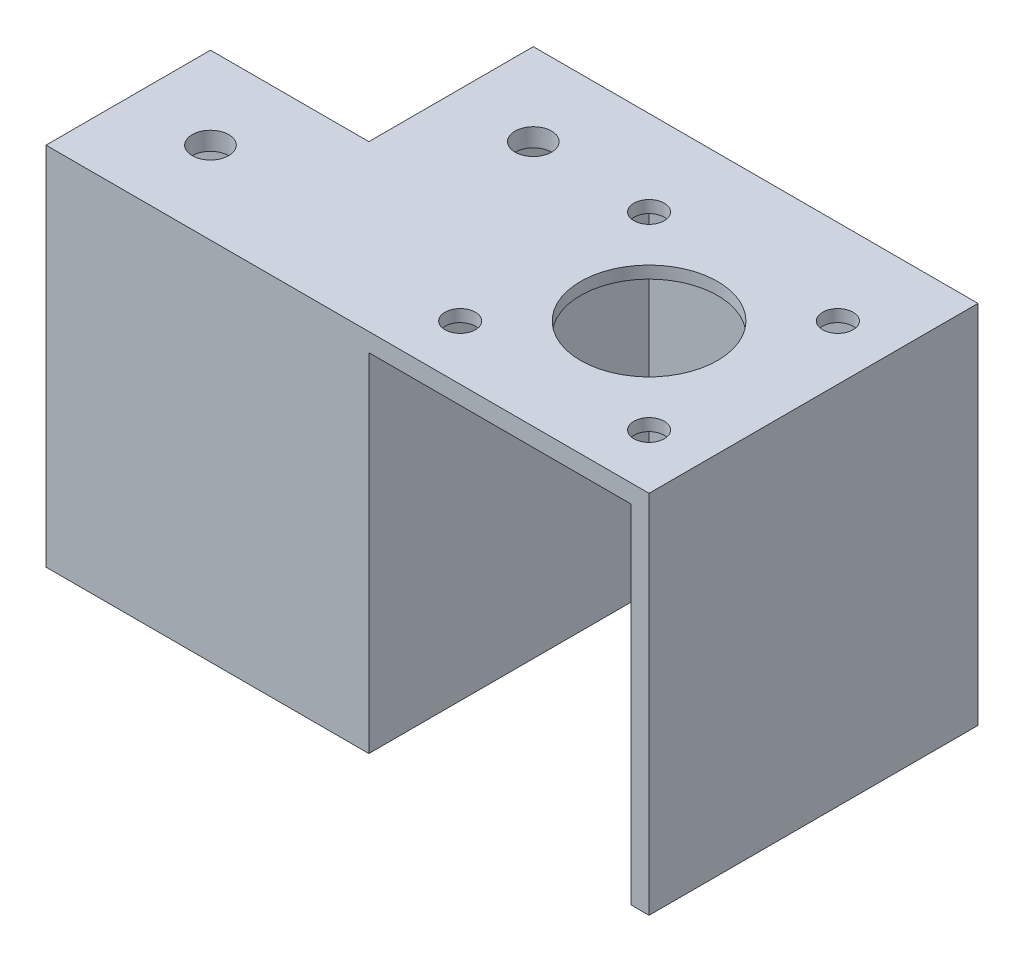
SolidWorks part; units mm, degrees
ref_plane "Front Plane" through (0, 0, 0) normal (0, 0, 1) x (1, 0, 0)
ref_plane "Top Plane" through (0, 0, 0) normal (0, 1, 0) x (1, 0, 0)
ref_plane "Right Plane" through (0, 0, 0) normal (1, 0, 0) x (0, 0, -1)
sketch "Sketch1" plane through (0, 0, 0) normal (0, 1, 0) x (1, 0, 0)
  line L0 (-15.5, 15.5) -> (15.5, 15.5) construction
  line L1 (-21.5, -21.5) -> (21.5, -21.5) construction
  line L2 (-21.5, -21.5) -> (-21.5, 21.5) construction
  line L3 (-21.5, 21.5) -> (21.5, 21.5) construction
  line L4 (21.5, -21.5) -> (21.5, 21.5) construction
  line L5 (-21.5, -21.5) -> (21.5, 21.5) construction
  line L6 (-21.5, 21.5) -> (21.5, -21.5) construction
  line L7 (-21.5, 0) -> (21.5, 0) construction
  line L8 (-21.5, 21.5) -> (-24.5, 29.5) construction
  line L10 (-24.5, 29.5) -> (48.5, 29.5)
  line L11 (-24.5, 29.5) -> (-24.5, -24.5)
  line L12 (-24.5, -24.5) -> (48.5, -24.5)
  line L13 (48.5, 29.5) -> (48.5, 2.5)
  line L14 (48.5, -24.5) -> (74.5, -24.5)
  line L16 (48.5, 2.5) -> (74.5, 2.5)
  line L17 (74.5, -24.5) -> (74.5, 2.5)
  circle A0 centre (15.5, 15.5) radius 2.5
  circle A1 centre (-15.5, 15.5) radius 2.5
  circle A2 centre (15.5, -15.5) radius 2.5
  circle A3 centre (-15.5, -15.5) radius 2.5
  circle A4 centre (0, 0) radius 11.25
  point P0 (0, 0)
  point P26 (74.5, -11)
  dimension "D3" = 5
  dimension "D8" = 22.5
  dimension "D1" = 43
  dimension "D2" = 31
  dimension "D4" = 8
  dimension "D5" = 3
  dimension "D6" = 3
  dimension "D7" = 27
  dimension "D9" = 27
  dimension "D10" = 26
extrude "Boss-Extrude1" add sketch "Sketch1" against normal blind 60 contours L13 L10 L11 L12 A2 A1 A0 A3
sketch "Sketch2" plane through (0, -60, 0) normal (0, -1, 0) x (1, 0, 0)
  line L0 (21.5, 21.5) -> (21.5, -21.5) construction
  line L1 (-21.5, -21.5) -> (21.5, -21.5) construction
  line L2 (-21.5, 21.5) -> (-21.5, -21.5) construction
  line L3 (-21.5, 21.5) -> (21.5, 21.5) construction
  line L4 (21.5, 21.5) -> (21.5, -21.5)
  line L5 (-21.5, -21.5) -> (21.5, -21.5)
  line L6 (-21.5, 21.5) -> (-21.5, -21.5)
  line L7 (-21.5, 21.5) -> (21.5, 21.5)
extrude "Cut-Extrude1" cut sketch "Sketch2" against normal offset from surface (58 mm away) 2 up to face at (0, 0, 11.25)
sketch "Sketch3" plane through (0, 0, -29.5) normal (0, 0, -1) x (-1, 0, 0)
  line L0 (24.5, 0) -> (-48.5, 0) construction
  line L1 (-45.5, -3) -> (-24.5, -3)
  line L2 (-45.5, -3) -> (-45.5, -24)
  line L3 (-45.5, -24) -> (-24.5, -24)
  line L4 (-24.5, -3) -> (-24.5, -24)
  line L5 (-48.5, -60) -> (-48.5, 0) construction
  dimension "D1" = 3
  dimension "D2" = 3
  dimension "D3" = 21
extrude "Cut-Extrude2" cut sketch "Sketch3" against normal offset from surface (51 mm away) 3 up to face at (25, -30, 24.5)
sketch "Sketch4" plane through (74.5, 0, 0) normal (1, 0, 0) x (0, 0, -1)
  line L0 (29.5, 0) -> (2.5, 0) construction
  line L1 (-0.5, -3) -> (-21.5, -3)
  line L2 (-0.5, -3) -> (-0.5, -24)
  line L3 (-0.5, -24) -> (-21.5, -24)
  line L4 (-21.5, -3) -> (-21.5, -24)
  line L6 (-24.5, -60) -> (-24.5, 0) construction
  dimension "D1" = 21
  dimension "D2" = 3
  dimension "D3" = 3
extrude "Cut-Extrude3" cut sketch "Sketch4" against normal up to surface (50 mm away) up to face at (24.5, -13.5, -4)
sketch "Sketch6" plane through (48.5, 0, 0) normal (1, 0, 0) x (0, 0, -1)
  line L1 (29.5, -60) -> (29.5, 0) construction
  line L2 (29.5, 0) -> (2.5, 0) construction
  line L3 (5.5, -24) -> (5.5, -3) construction
  line L12 (26.5, -3) -> (26.5, -24) construction
  line L13 (5.5, -3) -> (26.5, -3) construction
  line L14 (26.5, -24) -> (5.5, -24) construction
  line L15 (16, -3) -> (16, -24) construction
  circle A0 centre (16, -13.5) radius 3
  dimension "D3" = 6
  dimension "D2" = 3
  dimension "D1" = 3
  dimension "D4" = 21
extrude "Cut-Extrude5" cut sketch "Sketch6" against normal up to next contours A0
sketch "Sketch7" plane through (0, 0, 0) normal (0, 1, 0) x (1, 0, 0)
  line L0 (-24.5, 29.5) -> (48.5, 29.5) construction
  line L3 (45.5, 26.5) -> (24.5, 26.5) construction
  line L6 (45.5, 26.5) -> (45.5, 5.5) construction
  line L7 (45.5, 5.5) -> (24.5, 5.5) construction
  line L8 (24.5, 26.5) -> (24.5, 5.5) construction
  line L13 (48.5, 29.5) -> (48.5, 2.5) construction
  line L15 (35, 26.5) -> (35, 5.5) construction
  circle A0 centre (35, 16) radius 3
  dimension "D6" = 6
  dimension "D1" = 3
  dimension "D2" = 3
  dimension "D3" = 21
extrude "Cut-Extrude6" cut sketch "Sketch7" against normal up to next
mirror "Mirror2" [suppressed]
delete or keep bodies "Body-Delete/Keep 1" [suppressed] type delete bodies bodies 109
sketch "Sketch8" plane through (0, 0, -2.5) normal (0, 0, -1) x (-1, 0, 0)
  line L1 (-71.5, -3) -> (-50.5, -3) construction
  line L2 (-71.5, -3) -> (-71.5, -24) construction
  line L3 (-71.5, -24) -> (-50.5, -24) construction
  line L4 (-50.5, -3) -> (-50.5, -24) construction
  line L5 (-74.5, -60) -> (-74.5, 0) construction
  line L6 (-48.5, 0) -> (-74.5, 0) construction
  line L7 (-61, -3) -> (-61, -24) construction
  circle A0 centre (-61, -13.5) radius 3
  dimension "D4" = 6
  dimension "D1" = 21
  dimension "D2" = 3
  dimension "D3" = 3
extrude "Cut-Extrude7" cut sketch "Sketch8" against normal up to next
sketch "Sketch9" plane through (0, 0, 0) normal (0, 1, 0) x (1, 0, 0)
  line L0 (74.5, -24.5) -> (74.5, 2.5) construction
  line L1 (50.5, -21.5) -> (71.5, -21.5) construction
  line L2 (50.5, -21.5) -> (50.5, -0.5) construction
  line L3 (50.5, -0.5) -> (71.5, -0.5) construction
  line L4 (71.5, -21.5) -> (71.5, -0.5) construction
  line L5 (48.5, 2.5) -> (74.5, 2.5) construction
  line L6 (61, -0.5) -> (61, -21.5) construction
  circle A0 centre (61, -11) radius 3
  dimension "D4" = 6
  dimension "D1" = 3
  dimension "D2" = 3
  dimension "D3" = 21
extrude "Cut-Extrude8" cut sketch "Sketch9" against normal up to next
mirror "Mirror3" about plane through (-24.5, -60, 0) normal (-1, 0, 0) of bodies 113
delete or keep bodies "Body-Delete/Keep 2" type delete bodies bodies 113
sketch "Sketch10" plane through (0, 0, 24.5) normal (0, 0, 1) x (1, 0, 0)
  line L0 (-24.5, -60) -> (-123.5, -60) construction
  line L1 (-27.5, -60) -> (-70.5, -60)
  line L2 (-27.5, -60) -> (-27.5, -3)
  line L3 (-27.5, -3) -> (-70.5, -3)
  line L4 (-70.5, -60) -> (-70.5, -3)
  line L5 (-24.5, -60) -> (-24.5, 0) construction
  line L6 (-24.5, 0) -> (-123.5, 0) construction
  dimension "D1" = 3
  dimension "D2" = 3
  dimension "D3" = 43
extrude "Cut-Extrude9" cut sketch "Sketch10" against normal up to next
sketch "Sketch11" [suppressed] plane through (0, 0, 24.5) normal (0, 0, 1) x (1, 0, 0)
  line L0 (-24.5, -60) -> (74.5, -60) construction
  line L1 (-21.5, -60) -> (21.5, -60)
  line L2 (-21.5, -60) -> (-21.5, -3)
  line L3 (-21.5, -3) -> (21.5, -3)
  line L4 (21.5, -60) -> (21.5, -3)
  line L5 (-24.5, 0) -> (74.5, 0) construction
  line L6 (-24.5, -60) -> (-24.5, 0) construction
  dimension "D1" = 3
  dimension "D2" = 3
  dimension "D3" = 43
extrude "Cut-Extrude10" [suppressed] cut sketch "Sketch11" against normal up to next
